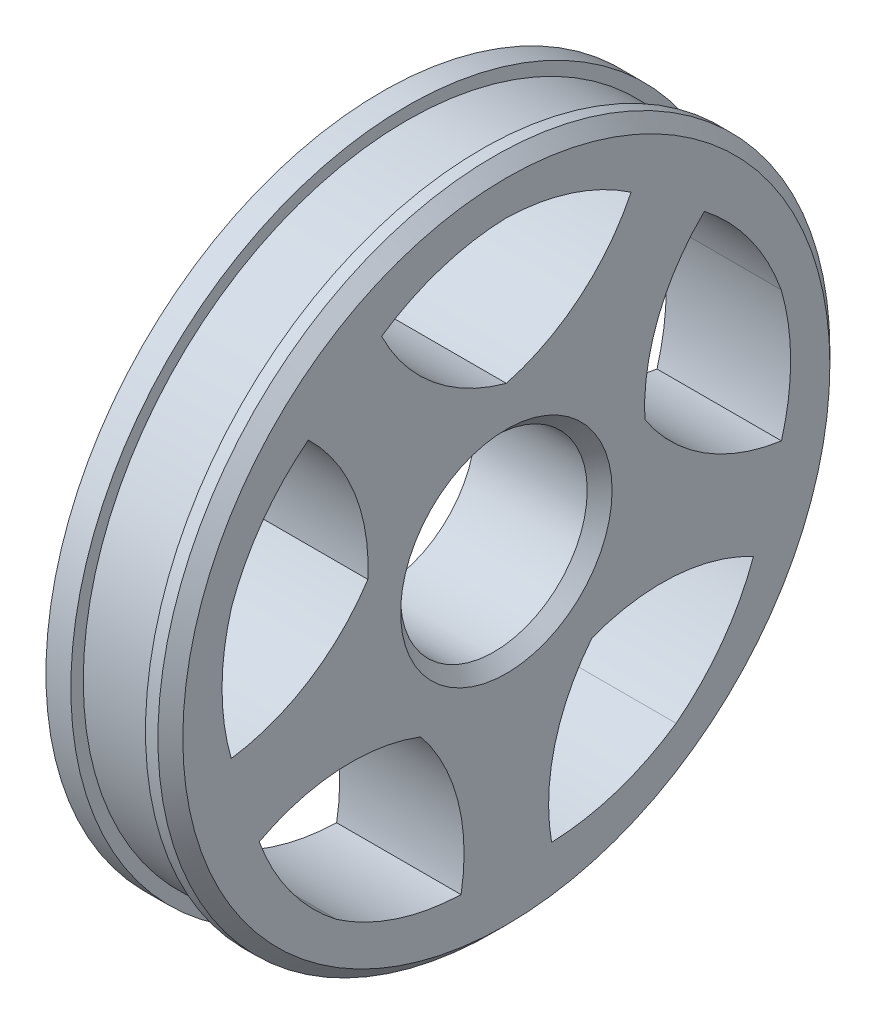
SolidWorks part; units mm, degrees
ref_plane "Front Plane" through (0, 0, 0) normal (0, 0, 1) x (1, 0, 0)
ref_plane "Top Plane" through (0, 0, 0) normal (0, 1, 0) x (1, 0, 0)
ref_plane "Right Plane" through (0, 0, 0) normal (1, 0, 0) x (0, 0, -1)
sketch "Sketch1" plane through (0, 0, 0) normal (1, 0, 0) x (0, 0, -1)
  circle A0 centre (0, 0) radius 13.5
  circle A1 centre (0, 0) radius 3.75
  dimension "D1" = 27
  dimension "D2" = 7.5
extrude "Boss-Extrude1" add sketch "Sketch1" along normal mid plane 5
sketch "Sketch2" plane through (0, 0, 0) normal (1, 0, 0) x (0, 0, -1)
  line L0 (0, 0) -> (0, 14.8201) construction
  arc A0 (0, 5.8497) -> (-5.0122, 9.994) centre (2.0377, 13.4173) cw
  arc A1 (-5.0122, 9.994) -> (0, 11.6087) centre (0.2591, 2.218) cw
  arc A2 (5.0122, 9.994) -> (0, 11.6087) centre (-0.2591, 2.218) ccw
  arc A3 (0, 5.8497) -> (5.0122, 9.994) centre (-2.0377, 13.4173) ccw
extrude "Cut-Extrude1" cut sketch "Sketch2" along normal through all both and the other way through all
pattern_circular "CirPattern1" count 5 over 360 about axis through (0, 0, 0) along (1, 0, 0) of "Cut-Extrude1"
chamfer "Chamfer1" distance 0.5 angle 45 2 edges at (2.5, 0, -13.5) (2.5, 0, -3.75)
sketch "Sketch4" plane through (0, 0, 0) normal (1, 0, 0) x (0, 0, -1)
  circle A0 centre (0, 0) radius 13.5
  circle A1 centre (0, 0) radius 13
  circle A2 centre (0, 0) radius 13.5 construction
  dimension "D1" = 0.5
extrude "Cut-Extrude3" cut sketch "Sketch4" against normal mid plane 3
equation "\"axis_diameter\"=5.66"
equation "\"padding\"=0.5"
